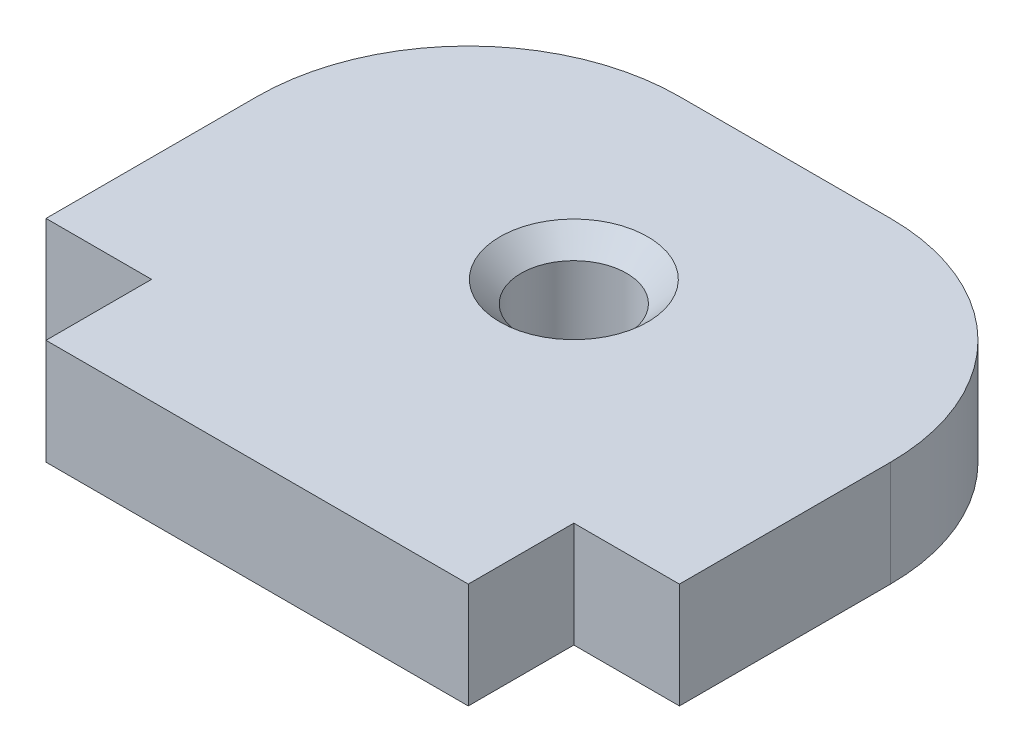
SolidWorks part; units mm, degrees
material "AISI 4340 Сталь, отожженная"
ref_plane "Спереди" through (0, 0, 0) normal (0, 0, 1) x (1, 0, 0)
ref_plane "Сверху" through (0, 0, 0) normal (0, 1, 0) x (1, 0, 0)
ref_plane "Справа" through (0, 0, 0) normal (1, 0, 0) x (0, 0, -1)
sketch "Эскиз1" plane through (0, 0, 0) normal (0, 1, 0) x (1, 0, 0)
  line L0 (-15, 5) -> (15, 20) construction
  line L1 (-15, 2.5) -> (-10, 2.5)
  line L2 (-10, 2.5) -> (-10, -2.5)
  line L3 (-10, -2.5) -> (10, -2.5)
  line L4 (10, 2.5) -> (10, -2.5)
  line L6 (-15, 2.5) -> (-15, 12.5)
  line L9 (5, 22.5) -> (-5, 22.5)
  line L11 (15, 2.5) -> (15, 12.5)
  line L13 (10, 2.5) -> (15, 2.5)
  circle A0 centre (0, 12.5) radius 3 construction
  arc A1 (15, 12.5) -> (5, 22.5) centre (5, 12.5) ccw
  arc A2 (-15, 12.5) -> (-5, 22.5) centre (-5, 12.5) cw
  point P0 (0, 0)
  point P6 (0, 2.5)
  point P16 (0, 12.5)
  dimension "D3" = 10
  dimension "D1" = 20
  dimension "D2" = 5
extrude "Бобышка-Вытянуть1" add sketch "Эскиз1" along normal blind 5
sketch "Эскиз4" plane through (0, 5, 0) normal (0, 1, 0) x (1, 0, 0)
  line L0 (-15, 2.5) -> (-10, 2.5) construction
  line L1 (0, 0) -> (0, 5.7749) construction
  point P0 (0, 12.5)
  dimension "D1" = 10
hole_wizard "Отверстие обработанное метчиком M61" positions "Эскиз4" profile "Эскиз3" tap size "M6" standard "DIN" end condition through all
sketch "Эскиз3" plane through (0, 5, -12.5) normal (1, 0, 0) x (0, 0, 1)
  line L0 (0, 0) -> (0, 5)
  line L1 (0, 5) -> (2.5, 5)
  line L2 (2.5, 5) -> (2.5, 1)
  line L3 (2.5, 1) -> (3.5, 0)
  line L5 (3.5, 0) -> (0, 0)
  line L6 (-2.5, 1) -> (-3.5, 0) construction
  line L11 (0, -6.35) -> (0, 107.95) construction
  dimension "Диаметр проходного сверла" = 5
  dimension "Глубина проходного сверла" = 5
  dimension "Диаметр передней зенковки" = 7
  dimension "Угол передней зенковки" = 90
cosmetic thread "Отверстие резьбы1" parameters "D2"=6
